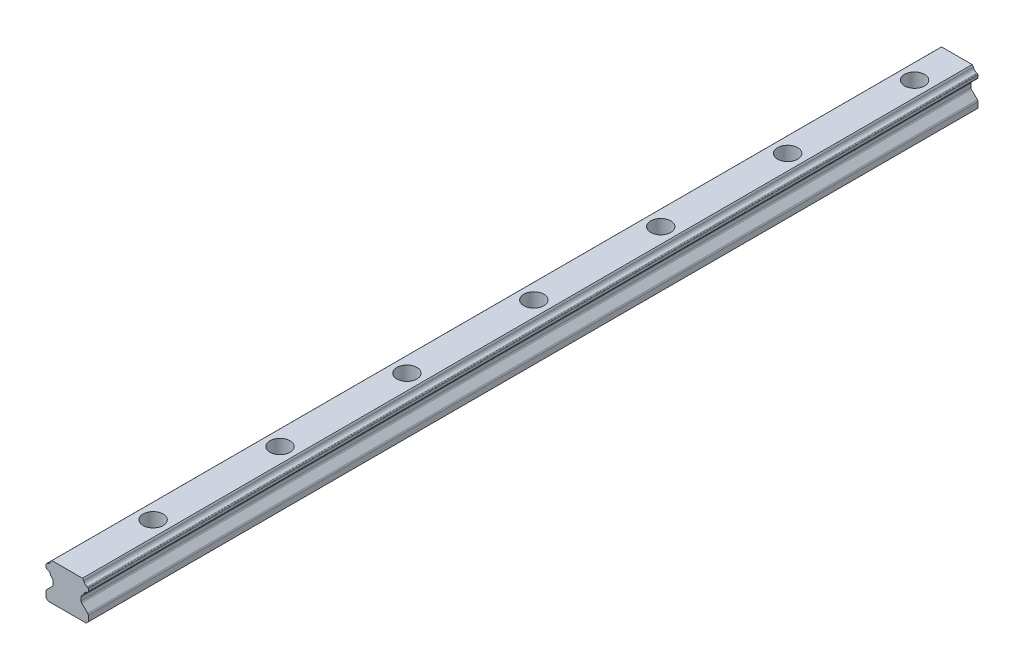
SolidWorks part; units mm, degrees
ref_plane "Front Plane" through (0, 0, 0) normal (0, 0, 1) x (1, 0, 0)
ref_plane "Top Plane" through (0, 0, 0) normal (0, 1, 0) x (1, 0, 0)
ref_plane "Right Plane" through (0, 0, 0) normal (1, 0, 0) x (0, 0, -1)
sketch "Model" plane through (0, 0, 0) normal (0, 0, 1) x (1, 0, 0)
  line L0 (-9, 0) -> (-10, 1)
  line L1 (9.7071, 4.3636) -> (6.8929, 7.1778)
  line L2 (-9.6906, 12.9499) -> (-9.8536, 13.1128)
  line L3 (7.6325, 17.0982) -> (7.2307, 17.5)
  line L4 (-6.8929, 10.1522) -> (-7.6302, 10.8894)
  line L5 (9.8536, 14.8772) -> (9.6785, 15.0522)
  line L6 (-9, 0) -> (9, 0)
  line L7 (-7.2307, 17.5) -> (7.2307, 17.5)
  line L8 (-9.8536, 14.8772) -> (-9.6785, 15.0522)
  line L9 (6.8929, 10.1522) -> (7.6302, 10.8894)
  line L10 (9, 0) -> (10, 1)
  line L11 (-9.7071, 4.3636) -> (-6.8929, 7.1778)
  line L12 (9.6906, 12.9499) -> (9.8536, 13.1128)
  line L13 (-7.6325, 17.0982) -> (-7.2307, 17.5)
  line L14 (-10, 1) -> (-10, 3.6565)
  line L15 (-10, 13.4664) -> (-10, 14.5236)
  line L16 (-6.6, 7.8849) -> (-6.6, 9.4451)
  line L17 (6.6, 7.8849) -> (6.6, 9.4451)
  line L18 (10, 1) -> (10, 3.6565)
  line L19 (10, 13.4664) -> (10, 14.5236)
  arc A0 (-7.8468, 11.2275) -> (-9.4318, 12.8125) centre (-9.8106, 10.8487) ccw
  arc A1 (-9.422, 15.1892) -> (-7.8482, 16.763) centre (-9.8101, 17.1511) ccw
  arc A2 (-10, 13.4664) -> (-9.8536, 13.1128) centre (-9.5, 13.4664) ccw
  arc A3 (-9.8536, 14.8772) -> (-10, 14.5236) centre (-9.5, 14.5236) ccw
  arc A4 (-9.6906, 12.9499) -> (-9.4318, 12.8125) centre (-9.3371, 13.3035) ccw
  arc A5 (-9.422, 15.1892) -> (-9.6785, 15.0522) centre (-9.3249, 14.6987) ccw
  arc A6 (-9.7071, 4.3636) -> (-10, 3.6565) centre (-9, 3.6565) ccw
  arc A7 (-6.8929, 7.1778) -> (-6.6, 7.8849) centre (-7.6, 7.8849) ccw
  arc A8 (-6.6, 9.4451) -> (-6.8929, 10.1522) centre (-7.6, 9.4451) ccw
  arc A9 (-7.6325, 17.0982) -> (-7.8482, 16.763) centre (-7.3547, 16.6825) ccw
  arc A10 (-7.8468, 11.2275) -> (-7.6302, 10.8894) centre (-7.3529, 11.3055) ccw
  arc A11 (7.6302, 10.8894) -> (7.8468, 11.2275) centre (7.3529, 11.3055) ccw
  arc A12 (7.8482, 16.763) -> (7.6325, 17.0982) centre (7.3547, 16.6825) ccw
  arc A13 (6.6, 7.8849) -> (6.8929, 7.1778) centre (7.6, 7.8849) ccw
  arc A14 (6.8929, 10.1522) -> (6.6, 9.4451) centre (7.6, 9.4451) ccw
  arc A15 (10, 3.6565) -> (9.7071, 4.3636) centre (9, 3.6565) ccw
  arc A16 (9.6785, 15.0522) -> (9.422, 15.1892) centre (9.3249, 14.6987) ccw
  arc A17 (9.4318, 12.8125) -> (9.6906, 12.9499) centre (9.3371, 13.3035) ccw
  arc A18 (9.8536, 13.1128) -> (10, 13.4664) centre (9.5, 13.4664) ccw
  arc A19 (10, 14.5236) -> (9.8536, 14.8772) centre (9.5, 14.5236) ccw
  arc A20 (7.8482, 16.763) -> (9.422, 15.1892) centre (9.8101, 17.1511) ccw
  arc A21 (9.4318, 12.8125) -> (7.8468, 11.2275) centre (9.8106, 10.8487) ccw
extrude "Boss-Extrude1" add sketch "Model" along normal blind 420.64
hole_wizard "CBORE for M5 Hex Head Bolt1" positions "Sketch4" profile "Sketch5" counterbore size "M5" standard "ANSI Metric" end condition through all
sketch "Sketch4" plane through (0, 17.5, 0) normal (0, 1, 0) x (1, 0, 0)
  line L0 (7.2307, 0) -> (-7.2307, 0) construction
  point P0 (0, -20)
  point P8 (0, 0)
  point P14 (0, -80)
  point P15 (0, -140)
  point P16 (0, -200)
  point P17 (0, -260)
  point P18 (0, -320)
  point P19 (0, -380)
  point P20 (0, -440)
  point P21 (0, -500)
  point P22 (0, -560)
  point P23 (0, -620)
  point P24 (0, -680)
  point P25 (0, -740)
  point P26 (0, -800)
  point P27 (0, -860)
  point P28 (0, -920)
  point P29 (0, -980)
  dimension "D1" = 20
  dimension "D3" = 60
  dimension "D2" = 17
sketch "Sketch5" plane through (0, 17.5, 20) normal (1, 0, 0) x (0, 0, 1)
  line L0 (0, 0) -> (0, 17.5)
  line L1 (0, 17.5) -> (3, 17.5)
  line L3 (3, 17.5) -> (3, 8.5)
  line L4 (3, 8.5) -> (4.75, 8.5)
  line L5 (4.75, 8.5) -> (4.75, 0)
  line L7 (4.75, 0) -> (0, 0)
  line L11 (0, -6.35) -> (0, 107.95) construction
  dimension "Thru Hole Dia." = 6
  dimension "Thru Hole Depth" = 17.5
  dimension "C'Bore Dia." = 9.5
  dimension "C'Bore Depth" = 8.5
